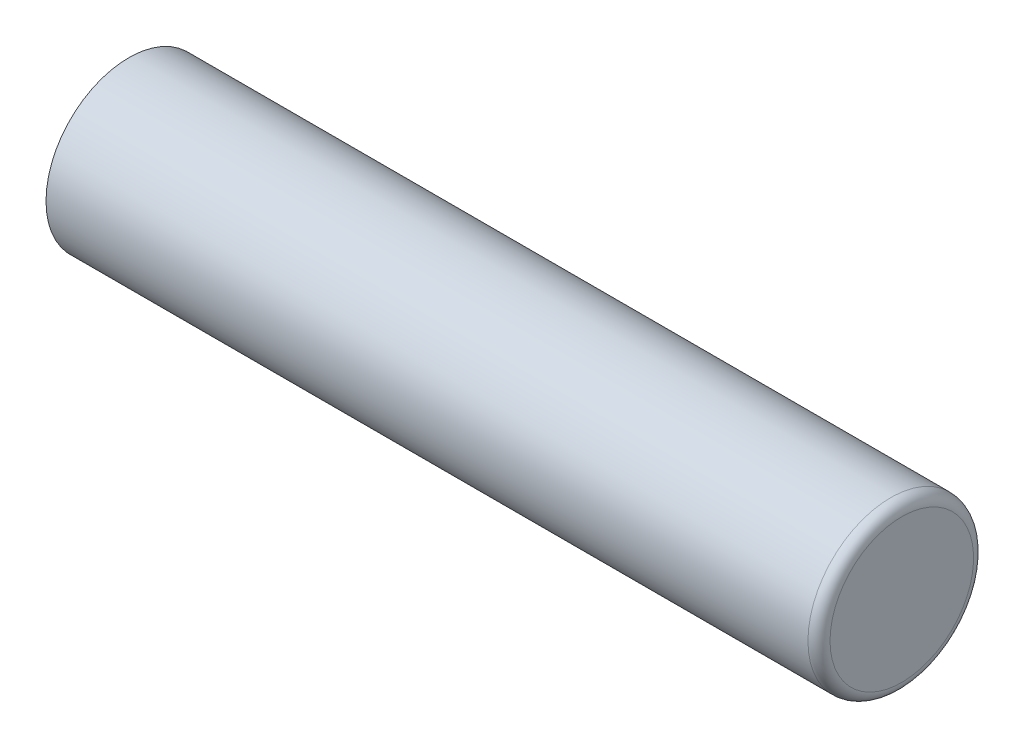
SolidWorks part; units mm, degrees
ref_plane "Plan de face" through (0, 0, 0) normal (0, 0, 1) x (1, 0, 0)
ref_plane "Plan de dessus" through (0, 0, 0) normal (0, 1, 0) x (1, 0, 0)
ref_plane "Plan de droite" through (0, 0, 0) normal (1, 0, 0) x (0, 0, -1)
sketch "Esquisse1" plane through (0, 0, 0) normal (0, 0, 1) x (1, 0, 0)
  line L0 (-5.7689, 0) -> (8.695, 0) construction
  line L3 (-0.34, 1.5) -> (13.66, 1.5)
  line L4 (13.66, 1.5) -> (13.66, 0)
  line L5 (-0.34, 0) -> (13.66, 0)
  line L6 (-0.34, 1.5) -> (-0.34, 0)
  dimension "D4" = 14
revolve "Révolution1" add sketch "Esquisse1" angle 360 about L0
fillet "Congé1" radius 0.2 1 edges at (13.66, 0, 1.5)
sketch "Esquisse2" plane through (-0.34, 0, 0) normal (-1, 0, 0) x (0, 0, 1)
  circle A0 centre (0, 0) radius 1.25
  dimension "D1" = 2.5
extrude "Enlèv. mat.-Extru.1" cut sketch "Esquisse2" against normal blind 0.5
